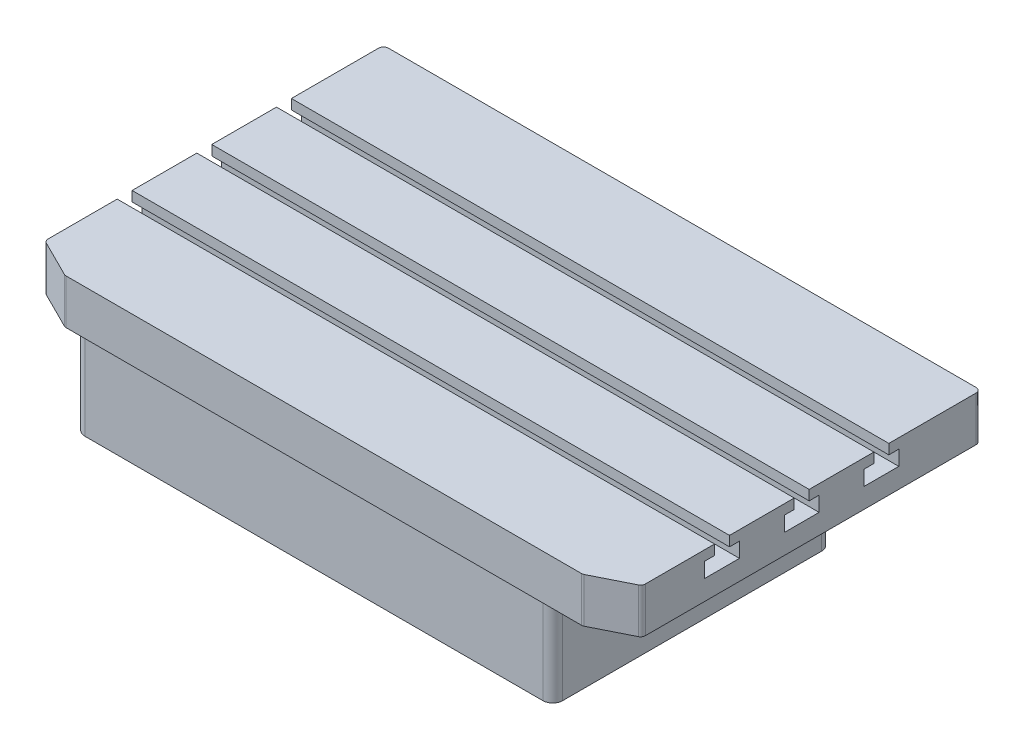
SolidWorks part; units mm, degrees
material "Malleable Cast Iron"
ref_plane "Front Plane" through (0, 0, 0) normal (0, 0, 1) x (1, 0, 0)
ref_plane "Top Plane" through (0, 0, 0) normal (0, 1, 0) x (1, 0, 0)
ref_plane "Right Plane" through (0, 0, 0) normal (1, 0, 0) x (0, 0, -1)
sketch "Sketch1" plane through (0, 0, 0) normal (0, 1, 0) x (1, 0, 0)
  line L1 (381, -228.6) -> (-381, -228.6)
  line L2 (381, -228.6) -> (381, 228.6)
  line L3 (381, 228.6) -> (-381, 228.6)
  line L4 (-381, -228.6) -> (-381, 228.6)
  line L5 (381, -228.6) -> (-381, 228.6) construction
  line L6 (381, 228.6) -> (-381, -228.6) construction
  point P0 (0, 0)
  dimension "D1" = 457.2
  dimension "D2" = 762
extrude "Boss-Extrude1" add sketch "Sketch1" along normal blind 57.15
sketch "Sketch2" plane through (0, 57.15, 0) normal (0, 1, 0) x (1, 0, 0)
  line L0 (-381, -203.2) -> (-330.2, -228.6)
  line L1 (-381, 228.6) -> (-381, -228.6) construction
  line L2 (-330.2, -228.6) -> (-381, -228.6)
  line L3 (-381, -228.6) -> (-381, -203.2)
  line L4 (0, 0) -> (0, 50000) construction
  line L5 (-381, -228.6) -> (381, -228.6) construction
  line L6 (330.2, -228.6) -> (381, -228.6)
  line L7 (381, -203.2) -> (330.2, -228.6)
  line L8 (381, -228.6) -> (381, -203.2)
  dimension "D1" = 50.8
  dimension "D2" = 25.4
extrude "Cut-Extrude1" cut sketch "Sketch2" against normal through all
sketch "Sketch3" plane through (381, 0, 0) normal (1, 0, 0) x (0, 0, -1)
  line L0 (-203.2, 57.15) -> (228.6, 57.15) construction
  line L1 (-123.825, 25.4) -> (-79.375, 25.4)
  line L2 (-123.825, 25.4) -> (-123.825, 44.45)
  line L3 (-123.825, 44.45) -> (-111.125, 44.45)
  line L4 (-79.375, 25.4) -> (-79.375, 44.45)
  line L5 (-111.125, 57.15) -> (-92.075, 57.15)
  line L6 (-111.125, 57.15) -> (-111.125, 44.45)
  line L8 (-92.075, 57.15) -> (-92.075, 44.45)
  line L9 (-92.075, 44.45) -> (-79.375, 44.45)
  line L10 (-228.6, 0) -> (-228.6, 57.15) construction
  line L11 (-22.225, 25.4) -> (-22.225, 44.45)
  line L12 (-22.225, 44.45) -> (-9.525, 44.45)
  line L13 (-9.525, 57.15) -> (-9.525, 44.45)
  line L14 (-9.525, 57.15) -> (9.525, 57.15)
  line L15 (9.525, 57.15) -> (9.525, 44.45)
  line L16 (9.525, 44.45) -> (22.225, 44.45)
  line L17 (22.225, 25.4) -> (22.225, 44.45)
  line L18 (-22.225, 25.4) -> (22.225, 25.4)
  line L19 (79.375, 25.4) -> (79.375, 44.45)
  line L20 (79.375, 44.45) -> (92.075, 44.45)
  line L21 (92.075, 57.15) -> (92.075, 44.45)
  line L22 (92.075, 57.15) -> (111.125, 57.15)
  line L23 (111.125, 57.15) -> (111.125, 44.45)
  line L24 (111.125, 44.45) -> (123.825, 44.45)
  line L25 (123.825, 25.4) -> (123.825, 44.45)
  line L26 (79.375, 25.4) -> (123.825, 25.4)
  point P11 (-101.6, 57.15)
  point P12 (-101.6, 25.4)
  dimension "D1" = 127
  dimension "D2" = 19.05
  dimension "D3" = 31.75
  dimension "D4" = 44.45
  dimension "D5" = 12.7
  dimension "D7" = 101.6
  dimension "D6" = 3
extrude "Cut-Extrude2" cut sketch "Sketch3" against normal through all
fillet "Fillet1" radius 6.35 6 edges at (381, 28.575, 203.2) (330.2, 28.575, 228.6) (-330.2, 28.575, 228.6) (-381, 28.575, 203.2) (381, 28.575, -228.6) (-381, 28.575, -228.6)
sketch "Sketch4" plane through (0, 0, 0) normal (0, -1, 0) x (1, 0, 0)
  line L0 (-381, -222.25) -> (-381, 199.2755) construction
  line L1 (-355.6, -165.1) -> (254, -165.1)
  line L2 (-355.6, -165.1) -> (-355.6, 190.5)
  line L3 (-355.6, 190.5) -> (254, 190.5)
  line L4 (254, -165.1) -> (254, 190.5)
  line L6 (374.65, -228.6) -> (-374.65, -228.6) construction
  dimension "D1" = 609.6
  dimension "D2" = 25.4
  dimension "D3" = 355.6
  dimension "D4" = 63.5
extrude "Boss-Extrude2" add sketch "Sketch4" along normal blind 146.05 separate body
fillet "Fillet2" radius 12.7 4 edges at (-355.6, -73.025, -165.1) (254, -73.025, -165.1) (254, -73.025, 190.5) (-355.6, -73.025, 190.5)
